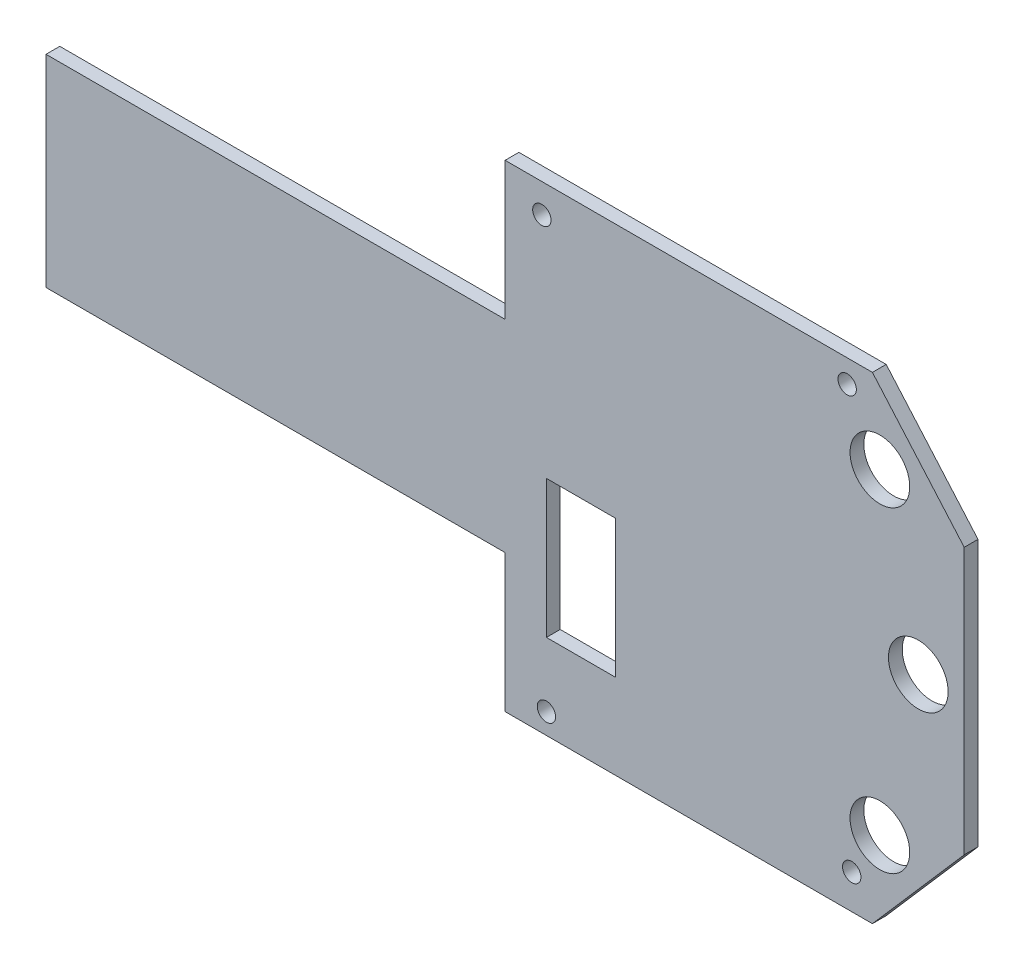
SolidWorks part; units mm, degrees
ref_plane "Plano frontal" through (0, 0, 0) normal (0, 0, 1) x (1, 0, 0)
ref_plane "Plano superior" through (0, 0, 0) normal (0, 1, 0) x (1, 0, 0)
ref_plane "Plano direito" through (0, 0, 0) normal (1, 0, 0) x (0, 0, -1)
sketch "Esboço1" plane through (0, 0, 0) normal (0, 0, 1) x (1, 0, 0)
  line L0 (0, 52) -> (200, 52) construction
  line L1 (100, 0) -> (180, 0)
  line L2 (0, 30) -> (0, 74)
  line L3 (100, 104) -> (180, 104)
  line L4 (200, 23) -> (200, 81)
  line L9 (200, 81) -> (180, 104)
  line L10 (200, 23) -> (180, 0)
  line L11 (0, 30) -> (100, 30)
  line L14 (0, 74) -> (100, 74)
  line L15 (100, 104) -> (100, 74)
  line L16 (100, 0) -> (100, 30)
  dimension "D1" = 200
  dimension "D2" = 104
  dimension "D3" = 58
  dimension "D4" = 20
  dimension "D5" = 100
  dimension "D6" = 30
extrude "Ressalto-extrusão1" add sketch "Esboço1" along normal blind 3
sketch "Esboço2" plane through (0, 0, 3) normal (0, 0, 1) x (1, 0, 0)
  line L0 (100, 30) -> (100, 0) construction
  line L1 (109, 48.5) -> (124, 48.5)
  line L2 (109, 48.5) -> (109, 18.5)
  line L3 (109, 18.5) -> (124, 18.5)
  line L4 (124, 48.5) -> (124, 18.5)
  line L5 (100, 0) -> (180, 0) construction
  dimension "D1" = 15
  dimension "D2" = 30
  dimension "D3" = 9
  dimension "D4" = 18.5
extrude "Corte-extrusão1" cut sketch "Esboço2" against normal blind 10
sketch "Esboço3" plane through (0, 0, 3) normal (0, 0, 1) x (1, 0, 0)
  line L0 (100, 30) -> (100, 0) construction
  line L1 (100, 0) -> (180, 0) construction
  circle A0 centre (109, 4.5) radius 2
  dimension "D1" = 4
  dimension "D3" = 4.5
  dimension "D2" = 9
extrude "Corte-extrusão2" cut sketch "Esboço3" against normal blind 10
sketch "Esboço4" plane through (0, 0, 3) normal (0, 0, 1) x (1, 0, 0)
  line L0 (100, 0) -> (180, 0) construction
  line L1 (100, 30) -> (100, 0) construction
  circle A0 centre (175.5, 7.5) radius 2
  dimension "D1" = 4
  dimension "D3" = 75.5
  dimension "D2" = 7.5
extrude "Corte-extrusão3" cut sketch "Esboço4" against normal blind 10
sketch "Esboço5" plane through (0, 0, 3) normal (0, 0, 1) x (1, 0, 0)
  line L1 (180, 104) -> (100, 104) construction
  line L2 (100, 104) -> (100, 74) construction
  circle A0 centre (108, 97.7) radius 2
  dimension "D1" = 4
  dimension "D2" = 6.3
  dimension "D3" = 8
extrude "Corte-extrusão4" cut sketch "Esboço5" against normal blind 10
sketch "Esboço6" plane through (0, 0, 3) normal (0, 0, 1) x (1, 0, 0)
  line L0 (180, 104) -> (100, 104) construction
  line L1 (100, 104) -> (100, 74) construction
  circle A0 centre (174.5, 99) radius 2
  dimension "D1" = 4
  dimension "D2" = 5
  dimension "D3" = 74.5
extrude "Corte-extrusão5" cut sketch "Esboço6" against normal blind 10
sketch "Esboço7" plane through (0, 0, 3) normal (0, 0, 1) x (1, 0, 0)
  line L0 (180, 104) -> (100, 104) construction
  line L1 (200, 23) -> (200, 81) construction
  line L2 (0, 52) -> (200, 52) construction
  line L3 (0, 74) -> (0, 30) construction
  circle A0 centre (181.63, 86.5) radius 6.5
  circle A1 centre (181.63, 17.5) radius 6.5
  dimension "D1" = 13
  dimension "D3" = 18.37
  dimension "D2" = 17.5
extrude "Corte-extrusão6" cut sketch "Esboço7" against normal blind 10
sketch "Esboço8" plane through (0, 0, 3) normal (0, 0, 1) x (1, 0, 0)
  line L2 (200, 23) -> (200, 81) construction
  circle A0 centre (189.9966, 52) radius 6.5
  circle A1 centre (181.63, 17.5) radius 6.5 construction
  circle A2 centre (181.63, 86.5) radius 6.5 construction
  point P8 (197.345, 90.2794)
  dimension "D1" = 13
  dimension "D3" = 35.5
  dimension "D4" = 10.0034
  dimension "D2" = 35.5
extrude "Corte-extrusão7" cut sketch "Esboço8" against normal blind 10
